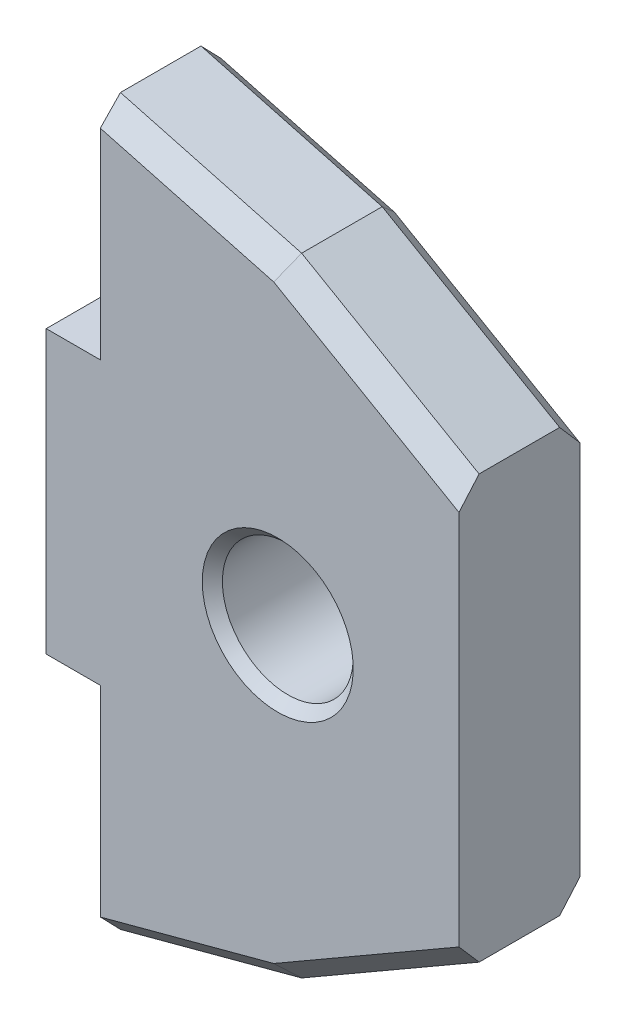
SolidWorks part; units mm, degrees
ref_plane "前视基准面" through (0, 0, 0) normal (0, 0, 1) x (1, 0, 0)
ref_plane "上视基准面" through (0, 0, 0) normal (0, 1, 0) x (1, 0, 0)
ref_plane "右视基准面" through (0, 0, 0) normal (1, 0, 0) x (0, 0, -1)
sketch "草图1" plane through (0, 0, 0) normal (0, 0, 1) x (1, 0, 0)
  line L0 (0, 0) -> (110.9931, 0) construction
  line L1 (55, 0) -> (-55, 0) construction
  line L2 (0, -14) -> (0, 14)
  line L3 (0, -55) -> (0, 55) construction
  line L4 (0, 14) -> (5.3731, 14)
  line L5 (5.3731, 14) -> (5.3731, 36)
  line L6 (5.3731, 36) -> (23.3731, 31.1769)
  line L7 (23.3731, 31.1769) -> (41, 21)
  line L8 (41, 21) -> (41, -21)
  line L9 (23.3731, -31.1769) -> (41, -21)
  line L10 (5.3731, -36) -> (23.3731, -31.1769)
  line L11 (5.3731, -14) -> (5.3731, -36)
  line L12 (0, -14) -> (5.3731, -14)
  point P14 (41, 0)
  dimension "D1" = 42
  dimension "D2" = 60
  dimension "D3" = 30
  dimension "D4" = 28
  dimension "D5" = 72
  dimension "D6" = 18
  dimension "D7" = 41
extrude "凸台-拉伸1" add sketch "草图1" along normal mid plane 12
sketch "草图2" plane through (0, 0, 6) normal (0, 0, 1) x (1, 0, 0)
  line L0 (6.6, 0) -> (-6.6, 0) construction
  line L1 (0, -6.6) -> (0, 6.6) construction
  circle A0 centre (23, 0) radius 6.5
  dimension "D1" = 13
  dimension "D2" = 23
extrude "切除-拉伸1" cut sketch "草图2" against normal through all
chamfer "倒角1" distance 1 angle 45 2 edges at (29.5, 0, 6) (29.5, 0, -6)
chamfer "倒角2" distance 2 angle 45 8 edges at (14.3731, -33.5885, -6) (32.1865, -26.0885, -6) (14.3731, -33.5885, 6) (32.1865, -26.0885, 6) (32.1865, 26.0885, -6) (14.3731, 33.5885, -6) (14.3731, 33.5885, 6) (32.1865, 26.0885, 6)
